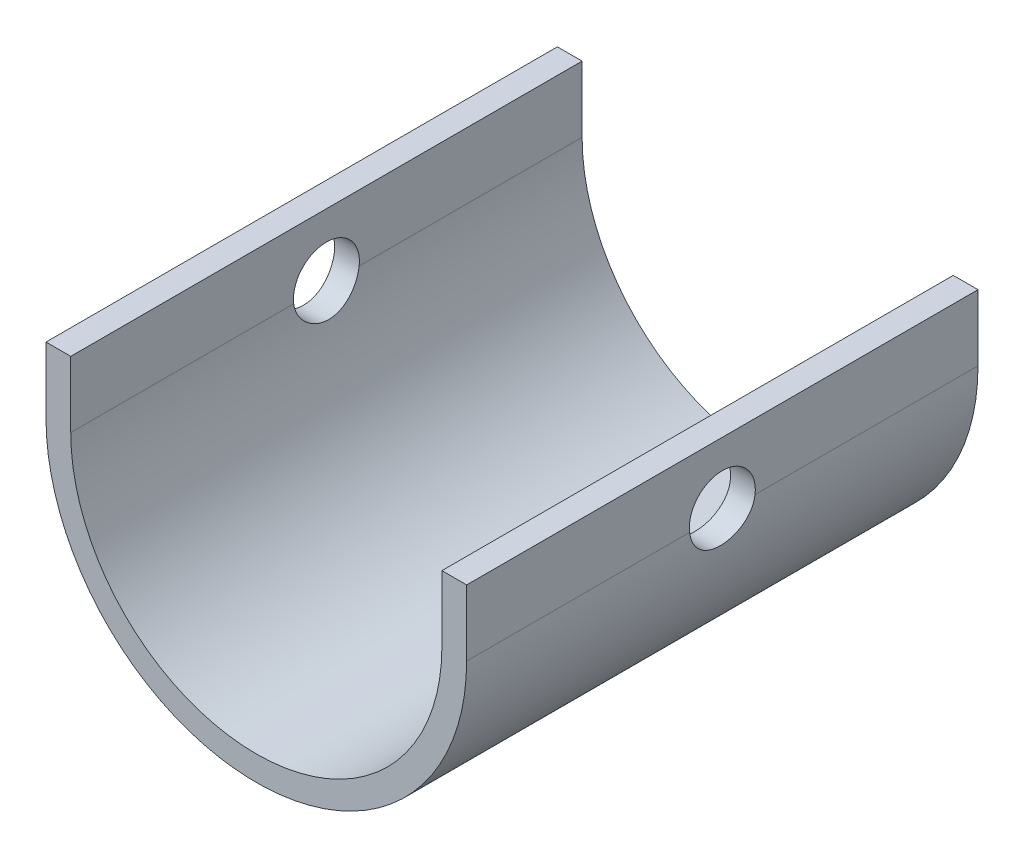
SolidWorks part; units mm, degrees
material "1060 Alloy"
ref_plane "Front Plane" through (0, 0, 0) normal (0, 0, 1) x (1, 0, 0)
ref_plane "Top Plane" through (0, 0, 0) normal (0, 1, 0) x (1, 0, 0)
ref_plane "Right Plane" through (0, 0, 0) normal (1, 0, 0) x (0, 0, -1)
sketch "Sketch1" plane through (0, 0, 0) normal (0, 0, 1) x (1, 0, 0)
  circle A0 centre (0, 0) radius 12.75
sketch "Sketch2" plane through (0, 0, 0) normal (0, 0, 1) x (1, 0, 0)
  circle A0 centre (0, 0) radius 11.25
extrude "Boss-Extrude1" add sketch "Sketch1" against normal blind 31 contours A0
extrude "Cut-Extrude1" cut sketch "Sketch2" against normal blind 31
sketch "Sketch3" plane through (0, 0, 0) normal (0, 0, 1) x (1, 0, 0)
  line L0 (55, 0) -> (-55, 0) construction
  line L1 (-12.75, 0) -> (13.313, 0)
  line L2 (-12.75, 0) -> (-12.75, 13.1229)
  line L3 (-12.75, 13.1229) -> (13.313, 13.1229)
  line L4 (13.313, 0) -> (13.313, 13.1229)
  circle A0 centre (0, 0) radius 12.75 construction
extrude "Cut-Extrude2" cut sketch "Sketch3" against normal blind 31
ref_plane "Plane1" through (0, 0, -15.5) normal (0, 0, 1) x (1, 0, 0)
ref_plane "Plane2" through (0, -11.25, 0) normal (0, 1, 0) x (1, 0, 0)
sketch "Sketch8" plane through (0, 0, 0) normal (0, 1, 0) x (1, 0, 0)
  line L0 (-44.2539, 0) -> (44.2539, 0) construction
  line L1 (-12.75, 31) -> (-11.25, 31)
  line L2 (-12.75, 31) -> (-12.75, 0)
  line L3 (-12.75, 0) -> (-11.25, 0)
  line L4 (-11.25, 31) -> (-11.25, 0)
  line L5 (-11.25, 31) -> (-11.25, 0) construction
  line L6 (12.75, 0) -> (12.75, 31) construction
  line L7 (11.25, 31) -> (12.75, 31)
  line L8 (11.25, 31) -> (11.25, 0)
  line L9 (11.25, 0) -> (12.75, 0)
  line L10 (12.75, 31) -> (12.75, 0)
extrude "Boss-Extrude3" add sketch "Sketch8" along normal blind 4
ref_plane "Plane4" through (0, 4, 0) normal (0, 1, 0) x (1, 0, 0)
ref_plane "Plane5" through (0, 0.25, 0) normal (0, 1, 0) x (1, 0, 0)
ref_plane "Plane6" through (12.75, 0, 0) normal (1, 0, 0) x (0, 0, -1)
ref_plane "Plane7" through (-12.75, 0, 0) normal (-1, 0, 0) x (0, 0, 1)
sketch "Sketch9" plane through (12.75, 0, 0) normal (1, 0, 0) x (0, 0, -1)
  line L0 (15.5, 9.2125) -> (15.5, -9.2125) construction
  line L1 (13.6313, 0.25) -> (-13.6313, 0.25) construction
  circle A0 centre (15.5, 0.25) radius 2
sketch "Sketch11" plane through (-12.75, 0, 0) normal (-1, 0, 0) x (0, 0, 1)
  circle A0 centre (-15.5, 0.25) radius 2
extrude "Cut-Extrude3" cut sketch "Sketch11" against normal blind 2
extrude "Cut-Extrude4" cut sketch "Sketch9" against normal blind 2
